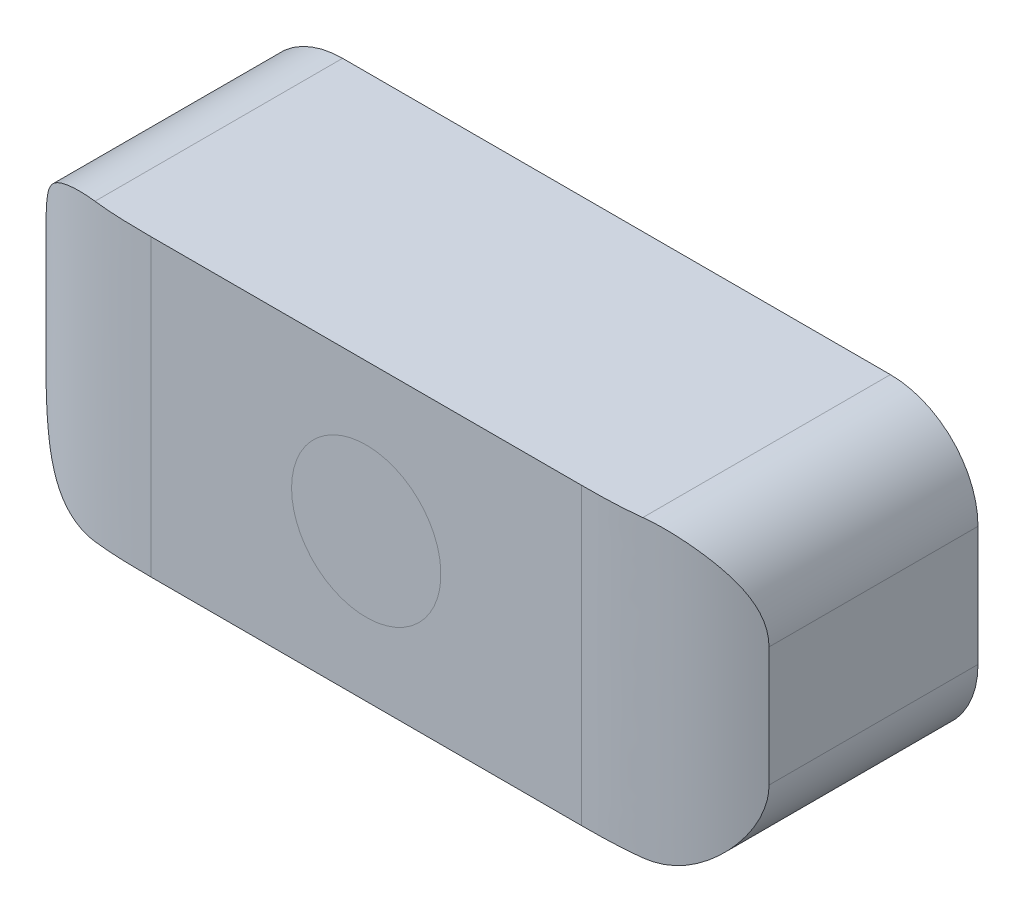
SolidWorks part; units mm, degrees
ref_plane "Front Plane" through (0, 0, 0) normal (0, 0, 1) x (1, 0, 0)
ref_plane "Top Plane" through (0, 0, 0) normal (0, 1, 0) x (1, 0, 0)
ref_plane "Right Plane" through (0, 0, 0) normal (1, 0, 0) x (0, 0, -1)
sketch "Sketch1" plane through (0, 0, 0) normal (1, 0, 0) x (0, 0, -1)
  line L1 (14.2875, -16.8275) -> (-14.2875, -16.8275)
  line L2 (14.2875, -16.8275) -> (14.2875, 16.8275)
  line L3 (14.2875, 16.8275) -> (-14.2875, 16.8275)
  line L4 (-14.2875, -16.8275) -> (-14.2875, 16.8275)
  line L5 (14.2875, -16.8275) -> (-14.2875, 16.8275) construction
  line L6 (14.2875, 16.8275) -> (-14.2875, -16.8275) construction
  point P0 (0, 0)
  dimension "D1" = 28.575
  dimension "D2" = 33.655
extrude "Boss-Extrude1" add sketch "Sketch1" along normal mid plane 82.55
fillet "Fillet1" radius 10 4 edges at (-41.275, -16.8275, 0) (41.275, -16.8275, 0) (-41.275, 16.8275, 0) (41.275, 16.8275, 0)
sketch "Sketch2" plane through (0, 16.8275, 0) normal (0, 1, 0) x (1, 0, 0)
  line L0 (-41.275, -14.2875) -> (-41.275, 14.2875) construction
  line L1 (31.275, -14.2875) -> (-31.275, -14.2875) construction
  line L2 (-8.2082, -14.2875) -> (-21.5659, -14.2875) construction
  line L3 (-41.275, -9.5737) -> (-47.4914, -9.5737)
  line L4 (-47.4914, -9.5737) -> (-47.4914, -17.6243)
  line L5 (-47.4914, -17.6243) -> (-24.5754, -17.6243)
  line L6 (-24.5754, -17.6243) -> (-24.5754, -14.2875)
  line L7 (0, 14.2875) -> (0, -14.2875) construction
  line L8 (31.275, 14.2875) -> (-31.275, 14.2875) construction
  line L9 (24.5754, -17.6243) -> (24.5754, -14.2875)
  line L10 (-41.275, 0) -> (41.275, 0) construction
  line L11 (41.275, 14.2875) -> (41.275, -14.2875) construction
  line L12 (47.4914, -17.6243) -> (24.5754, -17.6243)
  line L13 (47.4914, -9.5737) -> (47.4914, -17.6243)
  line L14 (41.275, -9.5737) -> (47.4914, -9.5737)
  spline S0 degree 3 poles (-41.275, -9.5737) (-36.6084, -13.6105) (-32.5383, -14.2875) (-24.5754, -14.2875) knots 0 0 0 0 1 1 1 1
  spline S1 degree 3 poles (41.275, -9.5737) (36.6084, -13.6105) (32.5383, -14.2875) (24.5754, -14.2875) knots 0 0 0 0 1 1 1 1
extrude "Cut-Extrude2" cut sketch "Sketch2" against normal through all
sketch "Sketch3" plane through (0, 0, 14.2875) normal (0, 0, 1) x (1, 0, 0)
  circle A0 centre (0, 0) radius 8.5246
split line "Split Line1"
